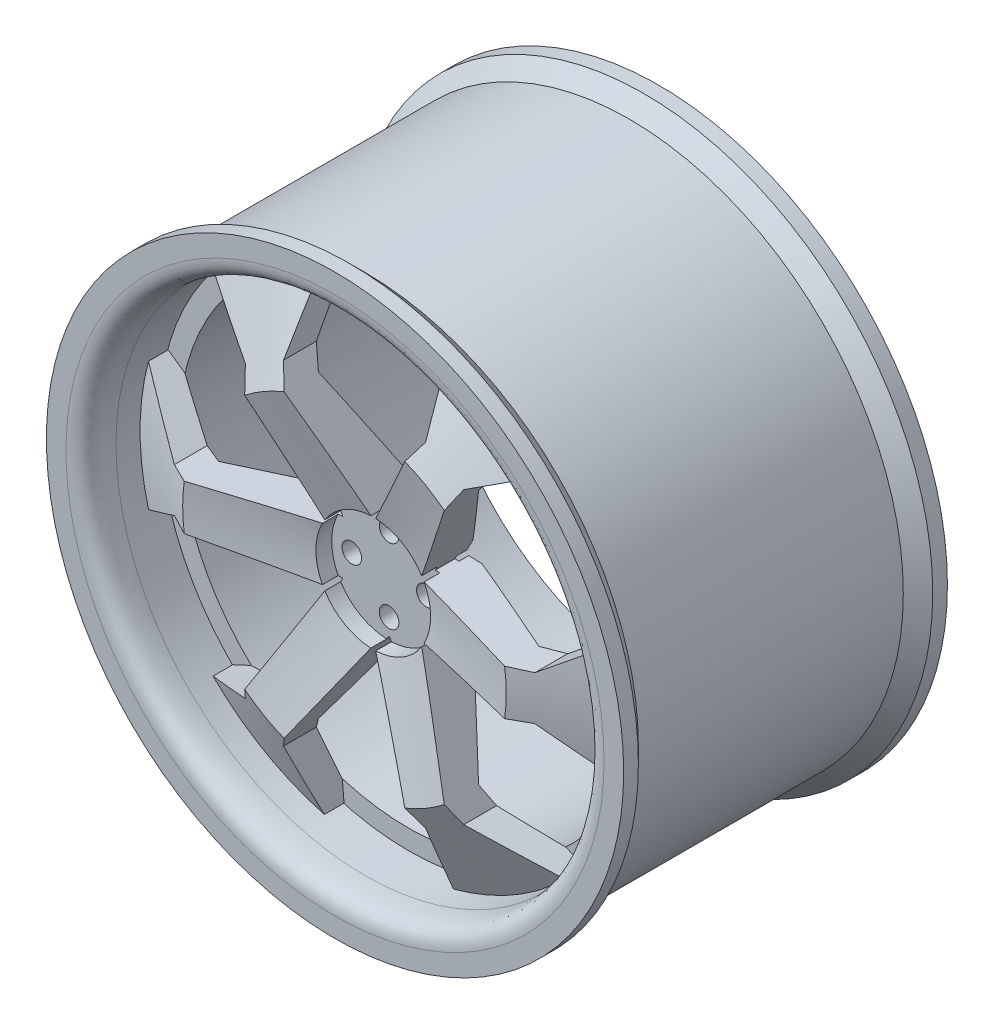
SolidWorks part; units mm, degrees
material "1060 Alloy"
ref_plane "Front Plane" through (0, 0, 0) normal (0, 0, 1) x (1, 0, 0)
ref_plane "Top Plane" through (0, 0, 0) normal (0, 1, 0) x (1, 0, 0)
ref_plane "Right Plane" through (0, 0, 0) normal (1, 0, 0) x (0, 0, -1)
ref_axis "Axis1" through (0, 0, 55) along (0, 0, -1)
sketch "Sketch1" plane through (0, 0, 0) normal (1, 0, 0) x (0, 0, -1)
  line L0 (0, 0) -> (0, 279.4) construction
  line L2 (-135.1, 279.4) -> (135.1, 279.4)
  line L3 (-135.1, 279.4) -> (-150.1, 294.4)
  line L4 (-150.1, 294.4) -> (-165.1, 294.4)
  line L5 (-90, 254.4) -> (-134.1, 254.4)
  line L6 (-90, 254.4) -> (-90, 234.4)
  line L7 (-90, 234.4) -> (0, 234.4)
  line L8 (-165.1, 294.4) -> (-165.1, 274.4)
  line L9 (150.1, 294.4) -> (165.1, 294.4)
  line L10 (135.1, 279.4) -> (150.1, 294.4)
  line L11 (165.1, 294.4) -> (165.1, 234.4)
  line L12 (165.1, 234.4) -> (0, 234.4)
  line L13 (-55, 0) -> (55, 0) construction
  spline S0 degree 3 poles (-165.1, 274.4) (-165.1, 256.0667) (-151.7667, 254.4) (-134.1, 254.4) knots 0 0 0 0 1 1 1 1
  dimension "D10" = 20
  dimension "55" = 53
  dimension "D11" = 55
  dimension "D1" = 279.4
  dimension "D2" = 165.1
  dimension "D3" = 15
  dimension "D4" = 20
  dimension "D6" = 20
  dimension "D7" = 90
  dimension "D8" = 45
  dimension "D9" = 31
revolve "Revolve2" add sketch "Sketch1" angle 360 about axis through (0, 0, 55) along (0, 0, -1)
sketch "Sketch2" plane through (0, 0, 0) normal (1, 0, 0) x (0, 0, -1)
  line L0 (-90, 253.8569) -> (-110.1, 253.8569)
  line L1 (-90, 254.4) -> (-90, -254.4) construction
  line L2 (-110.1, 253.8569) -> (-155.5, 165)
  line L3 (-155.5, 165) -> (-110, 0)
  line L4 (135.1, 0) -> (-135.1, 0) construction
  line L5 (-90, 253.8569) -> (-90, 234.7058)
  line L6 (-120.5, 165) -> (-80, 70)
  line L8 (-80, 70) -> (-80, 0)
  line L9 (-55, 0) -> (55, 0) construction
  line L10 (-90, 234.7058) -> (-120.5, 165)
  line L11 (-165.1, 294.4) -> (-165.1, -294.4) construction
  line L12 (-80, 0) -> (-110, 0)
  dimension "D1" = 155.5
  dimension "D2" = 165
  dimension "D3" = 55
  dimension "D4" = 70
  dimension "D5" = 110
  dimension "30" = 30
  dimension "D6" = 35
revolve "Revolve3" add sketch "Sketch2" angle 360 about axis through (0, 0, 55) along (0, 0, -1)
fillet "Fillet1" [suppressed] radius 50
fillet "Fillet2" [suppressed] radius 50
sketch "Sketch3" plane through (0, 0, 165.1) normal (0, 0, 1) x (1, 0, 0)
  line L0 (0, 0) -> (0, 336.0559) construction
  line L1 (-72.435, 170.4202) -> (0, 54.5)
  line L2 (-72.435, 170.4202) -> (-64, 266.8321)
  line L3 (72.435, 170.4202) -> (0, 54.5)
  line L4 (72.435, 170.4202) -> (64, 266.8321)
  circle A0 centre (0, 0) radius 274.4 construction
  arc A1 (64, 266.8321) -> (-64, 266.8321) centre (0, 0) ccw
  dimension "D1" = 5
  dimension "D2" = 64
  dimension "D3" = 32
  dimension "D4" = 54.5
extrude "Cut-Extrude1" cut sketch "Sketch3" against normal through all
fillet "Fillet3" [suppressed] radius 40
fillet "Fillet5" [suppressed] radius 15
pattern_circular "CirPattern1" count 6 over 360 about axis through (0, 0, 0) along (0, 0, 1) of "Cut-Extrude1", "Fillet3", "Fillet5"
sketch "Sketch4" plane through (0, 0, 80) normal (0, 0, -1) x (-1, 0, 0)
  line L0 (0, 0) -> (-76, 0) construction
  circle A0 centre (-38, 0) radius 10
  circle A1 centre (0, 38) radius 10
  circle A2 centre (38, 0) radius 10
  circle A3 centre (0, -38) radius 10
  point P14 (0, 0)
  dimension "D2" = 20
  dimension "D1" = 38
  dimension "D3" = 4
extrude "Cut-Extrude2" cut sketch "Sketch4" against normal through all
sketch "Sketch5" plane through (0, 0, 0) normal (1, 0, 0) x (0, 0, -1)
  line L0 (0, 0) -> (0, 400) construction
  dimension "D1" = 400
sketch "Sketch6" plane through (0, 0, 80) normal (0, 0, -1) x (-1, 0, 0)
  circle A0 centre (0, 0) radius 58.0596
extrude "Cut-Extrude3" cut sketch "Sketch6" against normal blind 10
ref_plane "Plane1" through (0, 0, 330) normal (0, 0, 1) x (1, 0, 0)
sketch "Sketch8" plane through (0, 0, 330) normal (0, 0, 1) x (1, 0, 0)
  circle A0 centre (0, 0) radius 58.5
  dimension "D1" = 117
extrude "Cut-Extrude4" cut sketch "Sketch8" against normal blind 220
